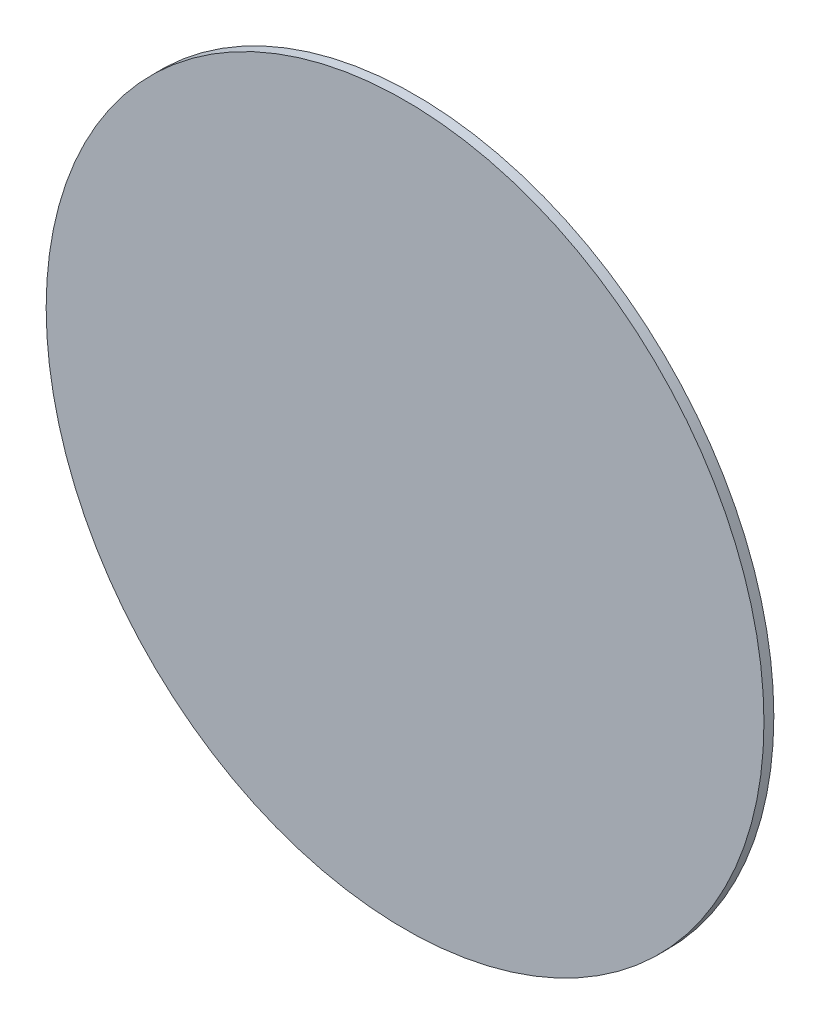
SolidWorks part; units mm, degrees
ref_plane "Plan de face" through (0, 0, 0) normal (0, 0, 1) x (1, 0, 0)
ref_plane "Plan de dessus" through (0, 0, 0) normal (0, 1, 0) x (1, 0, 0)
ref_plane "Plan de droite" through (0, 0, 0) normal (1, 0, 0) x (0, 0, -1)
sketch "Esquisse1" plane through (0, 0, 0) normal (0, 0, 1) x (1, 0, 0)
  line L3 (-49.9432, 96.8849) -> (-50.4746, 96.6091) construction
  circle A0 centre (0, 0) radius 109
  dimension "D1" = 218
extrude "Boss.-Extru.1" add sketch "Esquisse1" along normal blind 3
